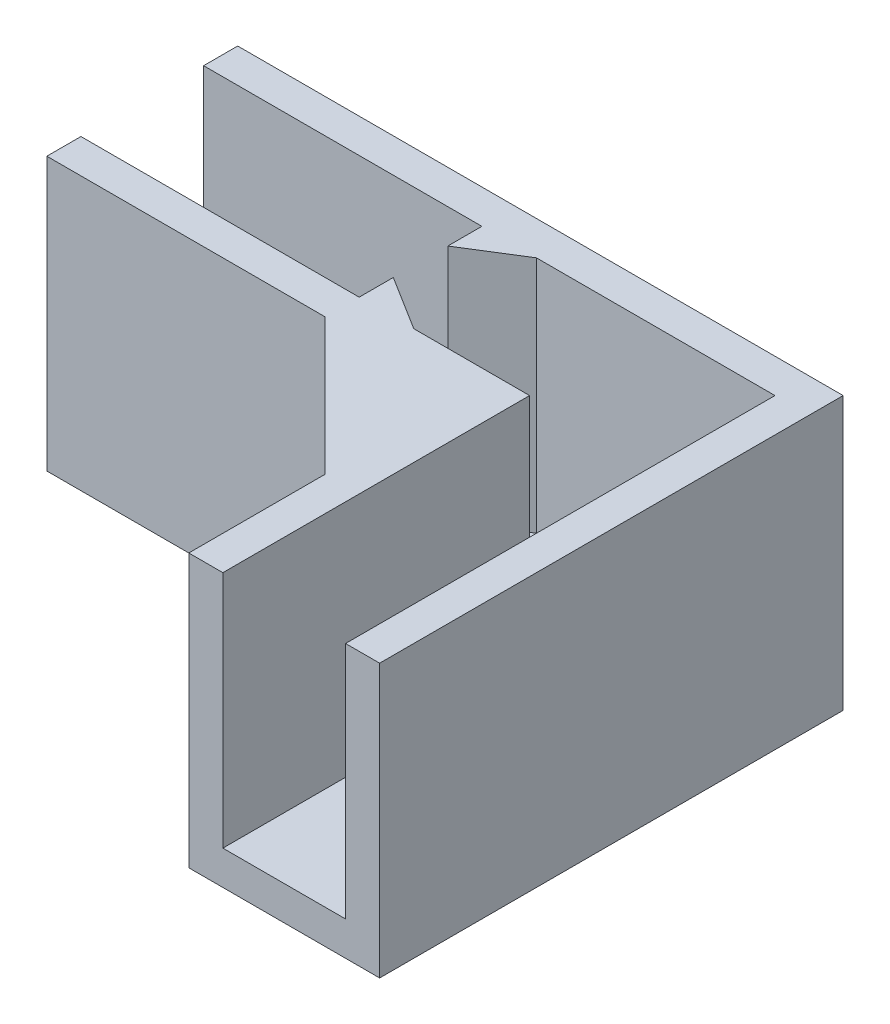
SolidWorks part; units mm, degrees
ref_plane "Alzado" through (0, 0, 0) normal (0, 0, 1) x (1, 0, 0)
ref_plane "Planta" through (0, 0, 0) normal (0, 1, 0) x (1, 0, 0)
ref_plane "Vista lateral" through (0, 0, 0) normal (1, 0, 0) x (0, 0, -1)
sketch "Croquis1" plane through (0, 0, 0) normal (0, 1, 0) x (1, 0, 0)
  line L2 (14, -14) -> (14, 14)
  line L3 (14, 14) -> (-14, 14)
  line L8 (-14, -14) -> (-14, -54)
  line L9 (-14, -54) -> (14, -54)
  line L10 (14, -14) -> (14, -54)
  line L11 (-14, 14) -> (-74.8225, 14)
  line L13 (-14, -14) -> (-74.8225, -14)
  line L14 (-74.8225, 14) -> (-74.8225, -14)
  point P0 (0, 0)
extrude "Saliente-Extruir1" add sketch "Croquis1" along normal blind 40
sketch "Croquis2" plane through (0, 40, 0) normal (0, 1, 0) x (1, 0, 0)
  line L0 (0, -1000) -> (0, -54) construction
  line L1 (-1000, 0) -> (-74.8225, 0) construction
  line L2 (-74.8225, 14) -> (-74.8225, -14) construction
  line L3 (9, 9) -> (-9, 9)
  line L4 (9, 9) -> (9, -9)
  line L9 (-9, 9) -> (-74.8225, 9)
  line L11 (-9, -9) -> (-74.8225, -9)
  line L12 (-74.8225, 9) -> (-74.8225, -9)
  line L13 (-14, -54) -> (14, -54) construction
  line L15 (-9, -9) -> (-9, -54)
  line L16 (-9, -54) -> (9, -54)
  line L17 (9, -9) -> (9, -54)
  line L18 (0, 9) -> (0, 49000) construction
  line L19 (9, 0) -> (49000, 0) construction
  line L21 (-9, 0) -> (0, 0) construction
  point P4 (0, 0)
extrude "Cortar-Extruir1" cut sketch "Croquis2" against normal blind 35
sketch "Croquis3" plane through (0, 40, 0) normal (0, 1, 0) x (1, 0, 0)
  line L0 (-34, -14) -> (-14, -34)
  line L2 (-14, -14) -> (-14, -54) construction
  line L3 (-14, -34) -> (-14, -14)
  line L4 (-14, -14) -> (-34, -14)
  line L5 (-74.8225, -14) -> (-14, -14) construction
  line L7 (-74.8225, 9) -> (-9, -9) construction
  line L9 (-34, -9) -> (-34, -4)
  line L10 (-74.8225, -9) -> (-9, -9) construction
  line L11 (-34, -4) -> (-26, -9)
  line L16 (-26, -9) -> (-34, -9)
  line L17 (-9, -9) -> (-9, 9) construction
  line L18 (9, 9) -> (-74.8225, 9) construction
  line L19 (-9, 9) -> (-74.8225, -9) construction
  line L20 (-1041.9113, 0) -> (48958.0887, 0) construction
  line L21 (-34, 4) -> (-26, 9)
  line L22 (-34, 9) -> (-34, 4)
  line L23 (-26, 9) -> (-34, 9)
  point P22 (-41.9113, 0)
  dimension "D1" = 45
  dimension "D2" = 20
  dimension "D3" = 20
  dimension "D4" = 8
  dimension "D5" = 5
extrude "Saliente-Extruir2" add sketch "Croquis3" against normal blind 40
